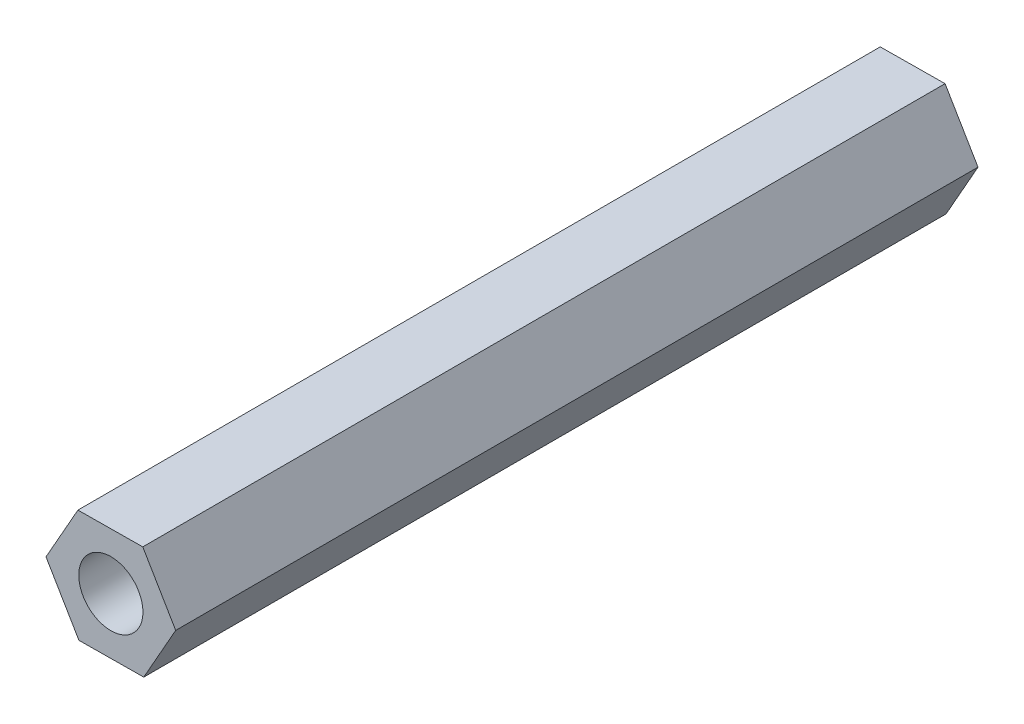
SolidWorks part; units mm, degrees
ref_plane "前视基准面" through (0, 0, 0) normal (0, 0, 1) x (1, 0, 0)
ref_plane "上视基准面" through (0, 0, 0) normal (0, 1, 0) x (1, 0, 0)
ref_plane "右视基准面" through (0, 0, 0) normal (1, 0, 0) x (0, 0, -1)
sketch "草图1" plane through (0, 0, 0) normal (0, 0, 1) x (1, 0, 0)
  line L1 (2.0515, -3.4821) -> (4.0413, 0.0356)
  line L2 (4.0413, 0.0356) -> (1.9898, 3.5177)
  line L3 (1.9898, 3.5177) -> (-2.0515, 3.4821)
  line L4 (-2.0515, 3.4821) -> (-4.0413, -0.0356)
  line L5 (-4.0413, -0.0356) -> (-1.9898, -3.5177)
  line L6 (-1.9898, -3.5177) -> (2.0515, -3.4821)
  circle A0 centre (0, 0) radius 3.5 construction
  circle A1 centre (0, 0) radius 2
extrude "凸台-拉伸1" add sketch "草图1" along normal blind 50
